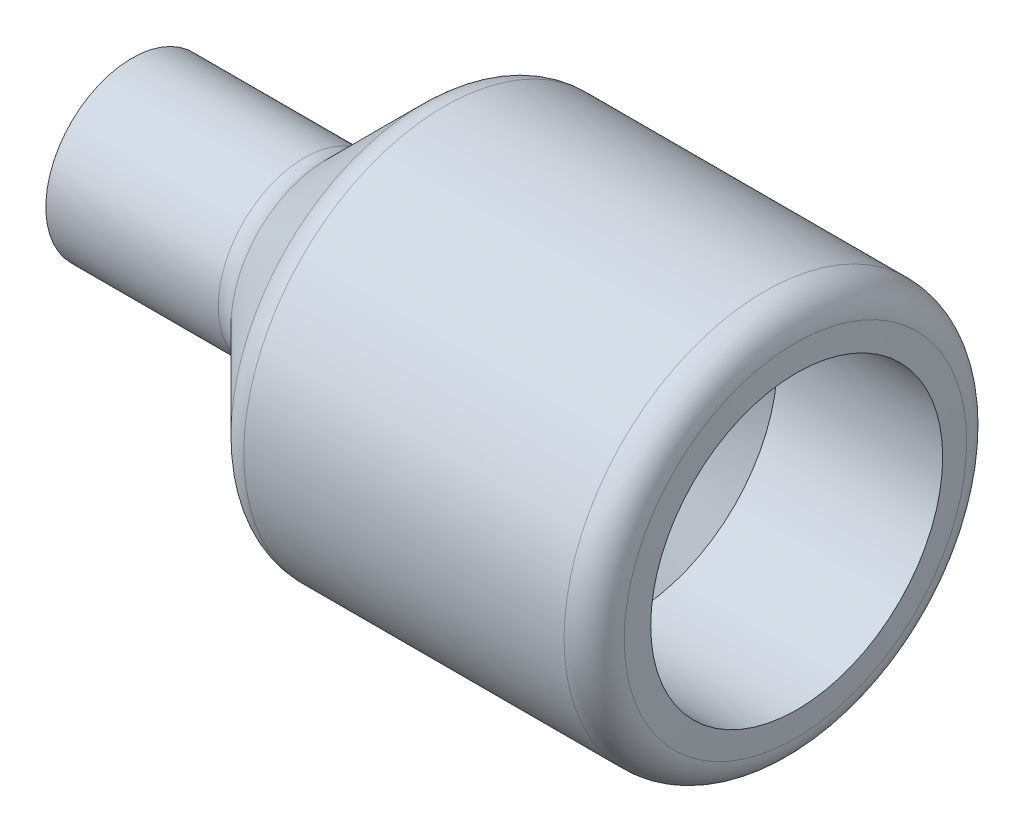
SolidWorks part; units mm, degrees
ref_plane "Front Plane" through (0, 0, 0) normal (0, 0, 1) x (1, 0, 0)
ref_plane "Top Plane" through (0, 0, 0) normal (0, 1, 0) x (1, 0, 0)
ref_plane "Right Plane" through (0, 0, 0) normal (1, 0, 0) x (0, 0, -1)
sketch "Sketch2" plane through (-264.6774, 57.5939, 41.335) normal (0, 0.8835, 0.4685) x (-1, 0, 0)
  line L0 (-138.8697, 106.529) -> (-86.072, 106.529) construction
  line L1 (-86.072, 117.529) -> (-86.072, 106.529) construction
  line L2 (-86.072, 106.529) -> (-86.072, 95.529) construction
  line L3 (-86.072, 117.529) -> (-86.072, 95.529) construction
  line L4 (-96.232, 111.2407) -> (-88.612, 111.2407)
  line L5 (-96.232, 111.2407) -> (-100.9437, 106.529)
  line L6 (-100.9437, 106.529) -> (-115.8632, 106.529)
  line L7 (-115.8632, 106.529) -> (-115.9731, 108.775)
  line L8 (-115.9731, 108.775) -> (-109.1668, 108.775)
  line L9 (-109.1668, 108.775) -> (-103.1578, 114.784)
  line L10 (-103.1578, 114.784) -> (-88.612, 114.784)
  line L11 (-88.612, 114.784) -> (-88.612, 111.2407)
  line L12 (-108.772, 109.529) -> (-109.272, 109.029) construction
  line L13 (-109.272, 109.029) -> (-111.9664, 109.029) construction
  spline S0 degree 8 poles (-115.772, 102.89) (-115.7767, 103.0205) (-115.7815, 103.1518) (-115.7862, 103.2841) (-115.7909, 103.4171) (-115.7957, 103.551) (-115.8004, 103.6856) (-115.8051, 103.8209) (-115.8388, 104.7885) (-115.8678, 105.645) (-115.8967, 106.5151) (-115.9257, 107.3879) (-115.9546, 108.2526) (-115.9836, 109.0984) (-116.0125, 109.9147) (-116.0707, 111.476) (-116.1, 112.2208) (-116.1292, 112.915) (-116.1585, 113.5496) (-116.1877, 114.1161) (-116.217, 114.6077) (-116.2462, 115.0183) (-116.3045, 115.6665) (-116.3335, 115.9057) (-116.3625, 116.0571) (-116.3915, 116.1182) (-116.4205, 116.088) (-116.4495, 115.9672) (-116.4785, 115.7577) (-116.5366, 115.168) (-116.5658, 114.7864) (-116.595, 114.3229) (-116.6241, 113.783) (-116.6533, 113.1733) (-116.6825, 112.5016) (-116.7116, 111.7769) (-116.7494, 110.7835) (-116.758, 110.5537) (-116.7666, 110.3204) (-116.7752, 110.0839) (-116.7837, 109.8444) (-116.7923, 109.6023) (-116.8009, 109.3577) (-116.8385, 108.2788) (-116.8675, 107.4217) (-116.8965, 106.5509) (-116.9254, 105.6773) (-116.9544, 104.8118) (-116.9834, 103.9651) (-117.0124, 103.1479) (-117.0706, 101.5857) (-117.0999, 100.8407) (-117.1291, 100.1462) (-117.1583, 99.5114) (-117.1876, 98.9446) (-117.2168, 98.4527) (-117.2461, 98.0417) (-117.3066, 97.3677) (-117.3378, 97.1165) (-117.3691, 96.9676) (-117.4003, 96.9241) (-117.4316, 96.9867) (-117.4628, 97.1543) (-117.4941, 97.4238) (-117.5562, 98.15) (-117.587, 98.6045) (-117.6178, 99.1476) (-117.6487, 99.772) (-117.6795, 100.4691) (-117.7103, 101.2289) (-117.7412, 102.0402) (-117.772, 102.89) knots 0 0 0 0 0 0 0 0 0 0.018929 0.018929 0.018929 0.018929 0.018929 0.018929 0.018929 0.13475 0.13475 0.13475 0.13475 0.13475 0.13475 0.13475 0.25175 0.25175 0.25175 0.25175 0.25175 0.25175 0.25175 0.36775 0.36775 0.36775 0.36775 0.36775 0.36775 0.36775 0.4844 0.4844 0.4844 0.4844 0.4844 0.4844 0.4844 0.518767 0.518767 0.518767 0.518767 0.518767 0.518767 0.518767 0.634687 0.634687 0.634687 0.634687 0.634687 0.634687 0.634687 0.751684 0.751684 0.751684 0.751684 0.751684 0.751684 0.751684 0.876677 0.876677 0.876677 0.876677 0.876677 0.876677 0.876677 1 1 1 1 1 1 1 1 1 weights 1 1 1 1 1 1 1 1 1 1 1 1 1 1 1 1 1 1 1 1 1 1 1 1 1 1 1 1 1 1 1 1 1 1 1 1 1 1 1 1 1 1 1 1 1 1 1 1 1 1 1 1 1 1 1 1 1 1 1 1 1 1 1 1 1 1 1 1 1 1 1 1 construction
  dimension "D1" = 9.4234
  dimension "D2" = 16.51
  dimension "D3" = 2.54
  dimension "D4" = 0.254
  dimension "D5" = 0.254
  dimension "D6" = 10.16
revolve "Revolve1" add sketch "Sketch2" angle 360 about L10
fillet "Fillet1" radius 1.27 3 edges at (-168.4454, 3.8154, 139.198) (-163.7337, 3.8154, 134.4863) (-148.8142, 3.8154, 134.4863)
